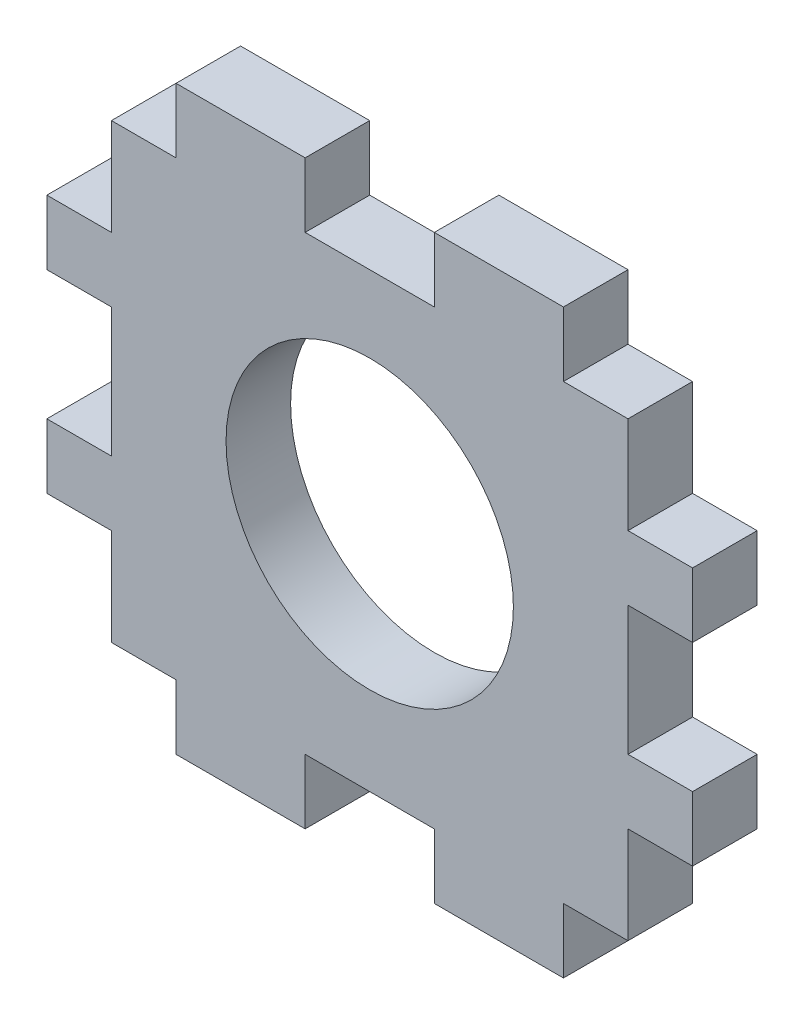
SolidWorks part; units mm, degrees
ref_plane "前视基准面" through (0, 0, 0) normal (0, 0, 1) x (1, 0, 0)
ref_plane "上视基准面" through (0, 0, 0) normal (0, 1, 0) x (1, 0, 0)
ref_plane "右视基准面" through (0, 0, 0) normal (1, 0, 0) x (0, 0, -1)
sketch "Model" plane through (0, 0, 0) normal (0, 0, 1) x (1, 0, 0)
  line L0 (1022.076, 566.4662) -> (1022.076, 569.4662)
  line L1 (1022.076, 569.4662) -> (1024.076, 569.4662)
  line L2 (1024.076, 569.4662) -> (1024.076, 571.4662)
  line L3 (1024.076, 571.4662) -> (1028.076, 571.4662)
  line L4 (1028.076, 571.4662) -> (1028.076, 569.4662)
  line L5 (1028.076, 569.4662) -> (1032.076, 569.4662)
  line L6 (1032.076, 569.4662) -> (1032.076, 571.4662)
  line L7 (1032.076, 571.4662) -> (1036.076, 571.4662)
  line L8 (1036.076, 571.4662) -> (1036.076, 569.4662)
  line L9 (1036.076, 569.4662) -> (1038.076, 569.4662)
  line L10 (1038.076, 569.4662) -> (1038.076, 566.4662)
  line L11 (1040.076, 566.4662) -> (1040.076, 564.4662)
  line L12 (1040.076, 564.4662) -> (1038.076, 564.4662)
  line L13 (1038.076, 564.4662) -> (1038.076, 560.4662)
  line L14 (1038.076, 560.4662) -> (1040.076, 560.4662)
  line L15 (1040.076, 560.4662) -> (1040.076, 558.4662)
  line L16 (1038.076, 555.4662) -> (1036.076, 555.4662)
  line L17 (1036.076, 555.4662) -> (1036.076, 553.4662)
  line L18 (1036.076, 553.4662) -> (1032.076, 553.4662)
  line L19 (1032.076, 553.4662) -> (1032.076, 555.4662)
  line L20 (1032.076, 555.4662) -> (1028.076, 555.4662)
  line L21 (1028.076, 555.4662) -> (1028.076, 553.4662)
  line L22 (1028.076, 553.4662) -> (1024.076, 553.4662)
  line L23 (1024.076, 553.4662) -> (1024.076, 555.4662)
  line L24 (1024.076, 555.4662) -> (1022.076, 555.4662)
  line L25 (1020.076, 558.4662) -> (1020.076, 560.4662)
  line L26 (1020.076, 560.4662) -> (1022.076, 560.4662)
  line L27 (1022.076, 560.4662) -> (1022.076, 564.4662)
  line L28 (1022.076, 564.4662) -> (1020.076, 564.4662)
  line L29 (1020.076, 564.4662) -> (1020.076, 566.4662)
  line L30 (1020.076, 566.4662) -> (1022.076, 566.4662)
  line L31 (1020.076, 558.4662) -> (1022.076, 558.4662)
  line L32 (1022.076, 558.4662) -> (1022.076, 555.4662)
  line L33 (1040.076, 566.4662) -> (1038.076, 566.4662)
  line L34 (1040.076, 558.4662) -> (1038.076, 558.4662)
  line L35 (1038.076, 558.4662) -> (1038.076, 555.4662)
  circle A0 centre (1030.076, 562.6456) radius 4.45
extrude "凸台-拉伸1" add sketch "Model" along normal blind 2
